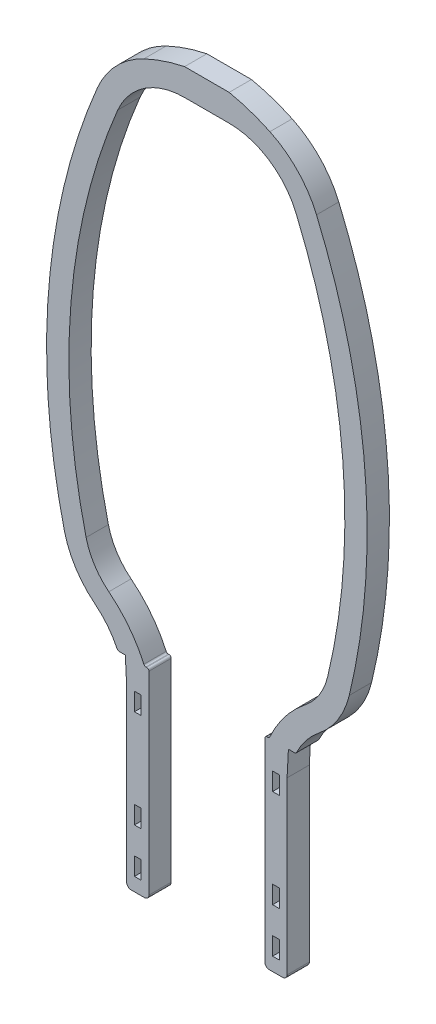
SolidWorks part; units mm, degrees
ref_plane "Front Plane" through (0, 0, 0) normal (0, 0, 1) x (1, 0, 0)
ref_plane "Top Plane" through (0, 0, 0) normal (0, 1, 0) x (1, 0, 0)
ref_plane "Right Plane" through (0, 0, 0) normal (1, 0, 0) x (0, 0, -1)
sketch "Sketch1" plane through (0, 0, 0) normal (0, 0, 1) x (1, 0, 0)
  line L0 (0, 0) -> (0, 115) construction
  line L1 (-13, -45) -> (-13, 0) construction
  line L2 (-18, 0) -> (-18, -45)
  line L3 (0, 0) -> (-18, 0) construction
  line L4 (0, 115) -> (-57.1655, 115) construction
  line L5 (-13, 0) -> (-27.0699, 24.3698) construction
  line L6 (-17.3301, -2.5) -> (-18, -45) construction
  line L7 (-18, -45) -> (-13, -45)
  line L8 (-13, -45) -> (-13, 0)
  line L9 (-5, 115) -> (0, 115)
  line L12 (18, -45) -> (13, -45)
  line L13 (13, -45) -> (13, 0)
  line L14 (5, 115) -> (0, 115)
  line L19 (-5, 121) -> (5, 121)
  line L20 (-5, 121) -> (-5, 115) construction
  line L21 (-20, 0) -> (-18, 0)
  line L22 (5, 121) -> (5, 115) construction
  line L23 (16.25, -6) -> (14.75, -6)
  line L24 (-16.25, -38) -> (-14.75, -38)
  line L25 (-16.25, -38) -> (-16.25, -42)
  line L26 (-16.25, -42) -> (-14.75, -42)
  line L27 (-14.75, -38) -> (-14.75, -42)
  line L28 (14.75, -38) -> (16.25, -38)
  line L29 (14.75, -38) -> (14.75, -42)
  line L30 (14.75, -42) -> (16.25, -42)
  line L31 (16.25, -38) -> (16.25, -42)
  line L32 (-16.25, -6) -> (-14.75, -6)
  line L33 (-16.25, -6) -> (-16.25, -10)
  line L34 (-16.25, -10) -> (-14.75, -10)
  line L35 (-14.75, -6) -> (-14.75, -10)
  line L36 (16.25, -6) -> (16.25, -10)
  line L37 (16.25, -10) -> (14.75, -10)
  line L38 (14.75, -6) -> (14.75, -10)
  line L39 (-14.75, -28) -> (-14.75, -32)
  line L40 (-16.25, -32) -> (-14.75, -32)
  line L41 (-16.25, -28) -> (-16.25, -32)
  line L42 (-16.25, -28) -> (-14.75, -28)
  line L43 (16.25, -28) -> (16.25, -32)
  line L44 (14.75, -32) -> (16.25, -32)
  line L45 (14.75, -28) -> (14.75, -32)
  line L46 (14.75, -28) -> (16.25, -28)
  line L47 (13, 0) -> (14, 0)
  line L48 (-13, 0) -> (-14, 0)
  line L49 (18, 0) -> (18, -45)
  line L50 (20, 0) -> (18, 0)
  arc A0 (-13, 0) -> (-22, 10.4498) centre (-45.0548, -18.5069) ccw construction
  arc A1 (-22, 10.4498) -> (-27.0993, 18.4498) centre (-12.9063, 21.8715) cw
  arc A2 (-12, 113.4188) -> (-5, 115) centre (-5, 98.7152) cw
  arc A3 (-27.0993, 18.4498) -> (-20, 105.0572) centre (107.8485, 50.9827) cw
  arc A4 (-20, 105.0572) -> (-12, 113.4188) centre (-4.9986, 98.7123) cw
  arc A5 (-17.3301, -2.5) -> (-25.1144, 6.5382) centre (-45.0548, -18.5069) ccw construction
  arc A6 (-25.1144, 6.5382) -> (-31.96, 17.278) centre (-12.9063, 21.8715) cw
  arc A7 (-31.96, 17.278) -> (-24.605, 107.005) centre (107.8485, 50.9827) cw
  arc A8 (-24.605, 107.005) -> (-14.1492, 117.9333) centre (-4.9986, 98.7123) cw
  arc A9 (-14.1492, 117.9333) -> (-5, 120) centre (-5, 98.7152) cw construction
  arc A10 (14.1492, 117.9333) -> (5, 120) centre (5, 98.7152) ccw construction
  arc A11 (24.605, 107.005) -> (14.1492, 117.9333) centre (4.9986, 98.7123) ccw
  arc A12 (31.96, 17.278) -> (24.605, 107.005) centre (-107.8485, 50.9827) ccw
  arc A13 (25.1144, 6.5382) -> (31.96, 17.278) centre (12.9063, 21.8715) ccw
  arc A15 (13, 0) -> (22, 10.4498) centre (45.0548, -18.5069) cw construction
  arc A16 (22, 10.4498) -> (27.0993, 18.4498) centre (12.9063, 21.8715) ccw
  arc A17 (27.0993, 18.4498) -> (20, 105.0572) centre (-107.8485, 50.9827) ccw
  arc A18 (20, 105.0572) -> (12, 113.4188) centre (4.9986, 98.7123) ccw
  arc A19 (12, 113.4188) -> (5, 115) centre (5, 98.7152) ccw
  arc A20 (-14.1492, 117.9333) -> (-5, 120) centre (-5, 98.7152) cw construction
  arc A23 (14.1492, 117.9333) -> (5, 121) centre (-3.0459, 81.8147) ccw
  arc A25 (-14.1492, 117.9333) -> (-5, 121) centre (3.0459, 81.8147) cw
  arc A26 (-25.1144, 6.5382) -> (-20, 0) centre (-36.2367, -7.4313) cw
  arc A27 (22, 10.4498) -> (14, 0) centre (38.8977, -10.7736) ccw
  arc A28 (-22, 10.4498) -> (-14, 0) centre (-38.8977, -10.7736) cw
  arc A29 (25.1144, 6.5382) -> (20, 0) centre (36.2367, -7.4313) ccw
  point P79 (-15.5, -38)
  dimension "D13" = 5
  dimension "D11" = 1
  dimension "D1" = 13
  dimension "D2" = 115
  dimension "D3" = 5
  dimension "D4" = 45
  dimension "D5" = 60
  dimension "D6" = 5
  dimension "D7" = 12
  dimension "D8" = 8
  dimension "D9" = 8
  dimension "D10" = 22
  dimension "D15" = 2
  dimension "D16" = 6
  dimension "D17" = 4
  dimension "D18" = 1.5
  dimension "D19" = 1.75
  dimension "D20" = 3
  dimension "D21" = 6
  dimension "D23" = 6
  dimension "D22" = 2
extrude "Boss-Extrude2" add sketch "Sketch1" along normal blind 5
fillet "Fillet1" radius 0.5 6 edges at (-13, 0, 2.5) (13, 0, 2.5) (14, 0, 2.5) (-14, 0, 2.5) (-20, 0, 2.5) (20, 0, 2.5)
chamfer "Chamfer1" distance 0.3 angle 87 2 edges at (18, 0, 2.5) (-18, 0, 2.5)
fillet "Fillet2" radius 1 4 edges at (-18, -45, 2.5) (-13, -45, 2.5) (18, -45, 2.5) (13, -45, 2.5)
